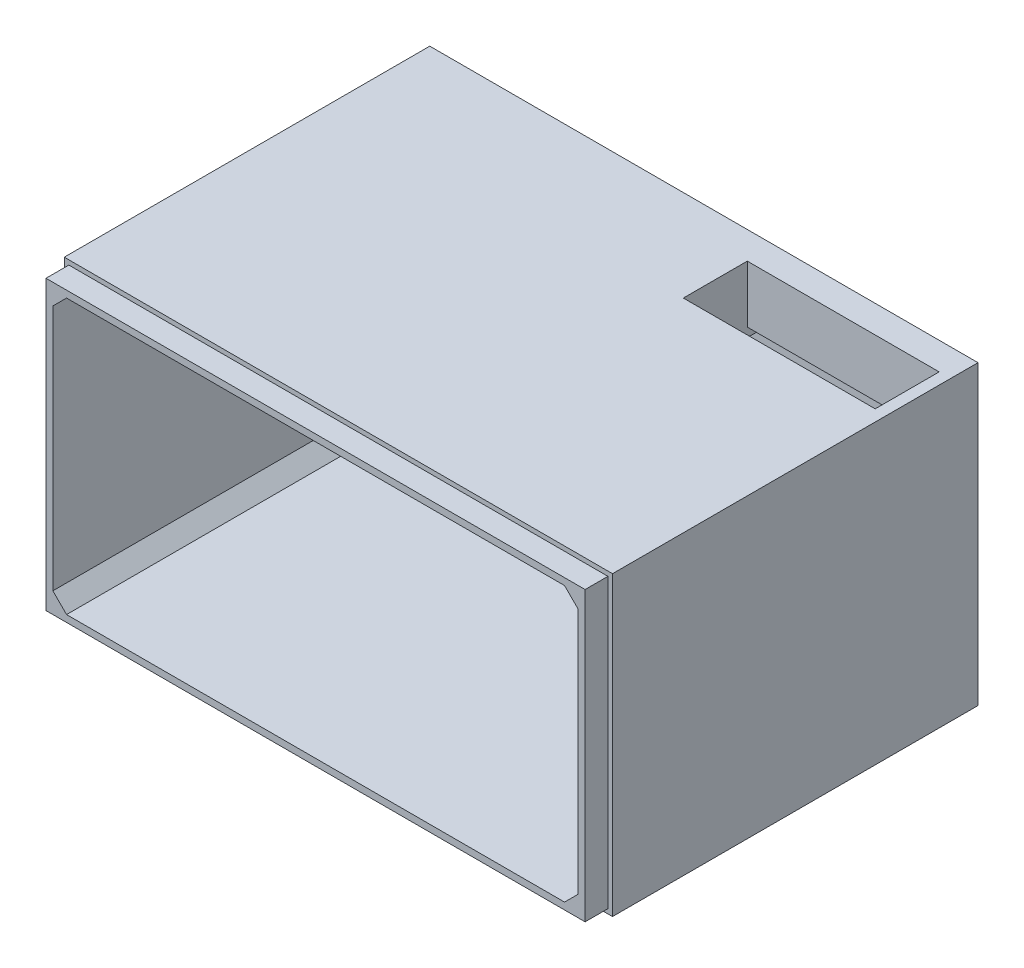
SolidWorks part; units mm, degrees
ref_plane "Front Plane" through (0, 0, 0) normal (0, 0, 1) x (1, 0, 0)
ref_plane "Top Plane" through (0, 0, 0) normal (0, 1, 0) x (1, 0, 0)
ref_plane "Right Plane" through (0, 0, 0) normal (1, 0, 0) x (0, 0, -1)
sketch "Sketch2" plane through (0, 0, 0) normal (0, 0, 1) x (1, 0, 0)
  line L1 (0, 0) -> (120, 0)
  line L2 (0, 0) -> (0, 65)
  line L3 (0, 65) -> (120, 65)
  line L4 (120, 0) -> (120, 65)
  dimension "D1" = 120
  dimension "D2" = 65
extrude "Boss-Extrude1" add sketch "Sketch2" along normal blind 85
sketch "Sketch3" plane through (0, 0, 85) normal (0, 0, 1) x (1, 0, 0)
  line L0 (120, 65) -> (0, 65) construction
  line L1 (2.5, 62.5) -> (117.5, 62.5)
  line L2 (2.5, 62.5) -> (2.5, 2.5)
  line L3 (2.5, 2.5) -> (117.5, 2.5)
  line L4 (117.5, 62.5) -> (117.5, 2.5)
  line L5 (0, 65) -> (0, 0) construction
  line L6 (120, 0) -> (120, 65) construction
  line L7 (0, 0) -> (120, 0) construction
  dimension "D1" = 2.5
  dimension "D2" = 2.5
  dimension "D3" = 2.5
  dimension "D4" = 2.5
extrude "Cut-Extrude1" cut sketch "Sketch3" against normal blind 82
sketch "Sketch4" plane through (0, 0, 0) normal (-1, 0, 0) x (0, 0, 1)
  line L0 (85, 0) -> (0, 0) construction
  line L1 (85, 65) -> (80, 65)
  line L2 (85, 65) -> (85, 0)
  line L3 (85, 0) -> (80, 0)
  line L4 (80, 65) -> (80, 0)
  dimension "D1" = 5
extrude "Cut-Extrude2" cut sketch "Sketch4" against normal blind 1
sketch "Sketch5" plane through (0, 65, 0) normal (0, 1, 0) x (1, 0, 0)
  line L0 (120, -85) -> (120, 0) construction
  line L1 (1, -85) -> (120, -85)
  line L2 (1, -85) -> (1, -80)
  line L3 (1, -80) -> (120, -80)
  line L4 (120, -85) -> (120, -80)
  dimension "D1" = 5
extrude "Cut-Extrude3" cut sketch "Sketch5" against normal blind 1
sketch "Sketch7" plane through (0, 0, 85) normal (0, 0, 1) x (1, 0, 0)
  line L0 (2.5, 62.5) -> (2.5, 59.5)
  line L1 (2.5, 62.5) -> (2.5, 2.5) construction
  line L2 (2.5, 59.5) -> (5.5, 62.5)
  line L3 (117.5, 62.5) -> (2.5, 62.5) construction
  line L4 (5.5, 62.5) -> (2.5, 62.5)
  line L5 (117.5, 62.5) -> (114.5, 62.5)
  line L6 (114.5, 62.5) -> (117.5, 59.5)
  line L7 (117.5, 2.5) -> (117.5, 62.5) construction
  line L8 (117.5, 59.5) -> (117.5, 62.5)
  line L9 (117.5, 5.5) -> (117.5, 2.5)
  line L10 (117.5, 2.5) -> (114.5, 2.5)
  line L11 (2.5, 2.5) -> (117.5, 2.5) construction
  line L12 (114.5, 2.5) -> (117.5, 5.5)
  line L13 (2.5, 2.5) -> (2.5, 5.5)
  line L14 (2.5, 5.5) -> (5.5, 2.5)
  line L15 (2.5, 2.5) -> (117.5, 2.5) construction
  line L16 (5.5, 2.5) -> (2.5, 2.5)
  dimension "D1" = 3
  dimension "D2" = 3
  dimension "D3" = 3
  dimension "D4" = 3
  dimension "D5" = 3
  dimension "D6" = 3
  dimension "D7" = 3
  dimension "D8" = 3
extrude "Boss-Extrude2" add sketch "Sketch7" against normal blind 85
sketch "Sketch9" plane through (120, 0, 0) normal (1, 0, 0) x (0, 0, -1)
  line L1 (-85, 64) -> (-80, 64)
  line L2 (-85, 64) -> (-85, 0)
  line L3 (-85, 0) -> (-80, 0)
  line L4 (-80, 64) -> (-80, 0)
extrude "Cut-Extrude4" cut sketch "Sketch9" against normal blind 1
sketch "Sketch10" plane through (0, 0, 0) normal (0, -1, 0) x (1, 0, 0)
  line L1 (119, 80) -> (1, 80)
  line L2 (119, 80) -> (119, 85)
  line L3 (119, 85) -> (1, 85)
  line L4 (1, 80) -> (1, 85)
extrude "Cut-Extrude5" cut sketch "Sketch10" against normal blind 1
sketch "Sketch11" plane through (0, 65, 0) normal (0, 1, 0) x (1, 0, 0)
  line L0 (120, 0) -> (0, 0) construction
  line L1 (117.5, -20) -> (75.5, -20)
  line L2 (117.5, -20) -> (117.5, -6)
  line L3 (117.5, -6) -> (75.5, -6)
  line L4 (75.5, -20) -> (75.5, -6)
  line L5 (120, -80) -> (120, 0) construction
  dimension "D1" = 42
  dimension "D2" = 6
  dimension "D3" = 2.5
  dimension "D4" = 14
extrude "Cut-Extrude6" cut sketch "Sketch11" against normal blind 10
sketch "Sketch12" plane through (0, 0, 6) normal (0, 0, 1) x (1, 0, 0)
  line L1 (75.5, 62.5) -> (117.5713, 62.5)
  line L2 (75.5, 62.5) -> (75.5, 52.5)
  line L3 (75.5, 52.5) -> (117.5713, 52.5)
  line L4 (117.5713, 62.5) -> (117.5713, 52.5)
  dimension "D1" = 10
extrude "Boss-Extrude3" add sketch "Sketch12" against normal blind 4
sketch "Sketch13" plane through (0, 0, 3) normal (0, 0, 1) x (1, 0, 0)
  line L0 (75.5, 62.5) -> (5.5, 62.5) construction
  line L1 (75.5, 52.5) -> (73.5, 52.5)
  line L2 (75.5, 52.5) -> (75.5, 62.5)
  line L3 (75.5, 62.5) -> (73.5, 62.5)
  line L4 (73.5, 52.5) -> (73.5, 62.5)
  dimension "D1" = 2
extrude "Boss-Extrude4" add sketch "Sketch13" along normal blind 17
sketch "Sketch14" plane through (0, 0, 20) normal (0, 0, 1) x (1, 0, 0)
  line L1 (73.5, 62.5) -> (117.9029, 62.5)
  line L2 (73.5, 62.5) -> (73.5, 52.5)
  line L3 (73.5, 52.5) -> (117.9029, 52.5)
  line L4 (117.9029, 62.5) -> (117.9029, 52.5)
extrude "Boss-Extrude5" add sketch "Sketch14" along normal blind 2
sketch "Sketch15" plane through (0, 52.5, 0) normal (0, -1, 0) x (1, 0, 0)
  line L1 (73.5, 22) -> (117.565, 22)
  line L2 (73.5, 22) -> (73.5, 14)
  line L3 (73.5, 14) -> (117.565, 14)
  line L4 (117.565, 22) -> (117.565, 14)
  dimension "D1" = 8
extrude "Boss-Extrude6" add sketch "Sketch15" along normal blind 2
sketch "Sketch16" plane through (0, 0, 3) normal (0, 0, 1) x (1, 0, 0)
  line L1 (73.5, 52.5) -> (75.5, 52.5)
  line L2 (73.5, 52.5) -> (73.5, 50.5)
  line L3 (73.5, 50.5) -> (75.5, 50.5)
  line L4 (75.5, 52.5) -> (75.5, 50.5)
  dimension "D1" = 2
  dimension "D2" = 2
extrude "Boss-Extrude7" add sketch "Sketch16" along normal blind 12
sketch "Sketch17" plane through (0, 52.5, 0) normal (0, 1, 0) x (1, 0, 0)
  line L0 (75.5, -14) -> (117.5, -14) construction
  line L1 (115.1126, -14) -> (98.1126, -14)
  line L2 (115.1126, -14) -> (115.1126, -18)
  line L3 (115.1126, -18) -> (98.1126, -18)
  line L4 (98.1126, -14) -> (98.1126, -18)
  dimension "D1" = 17
  dimension "D2" = 4
extrude "Cut-Extrude7" cut sketch "Sketch17" against normal blind 5
